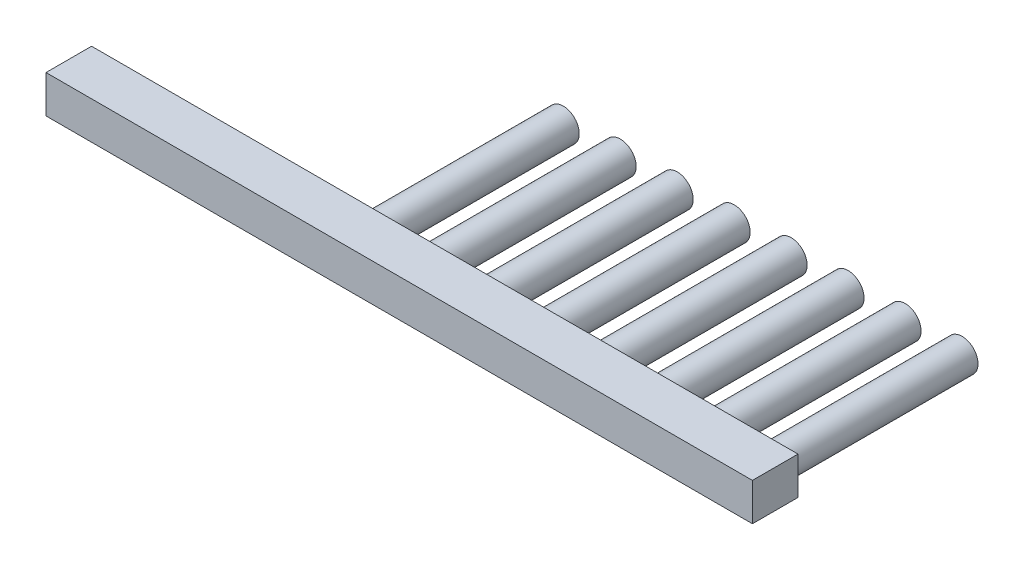
SolidWorks part; units mm, degrees
ref_plane "Front Plane" through (0, 0, 0) normal (0, 0, 1) x (1, 0, 0)
ref_plane "Top Plane" through (0, 0, 0) normal (0, 1, 0) x (1, 0, 0)
ref_plane "Right Plane" through (0, 0, 0) normal (1, 0, 0) x (0, 0, -1)
sketch "Sketch2" plane through (0, 0, 0) normal (0, 0, 1) x (1, 0, 0)
  line L1 (155, 8.25) -> (-155, 8.25)
  line L2 (155, 8.25) -> (155, -8.25)
  line L3 (155, -8.25) -> (-155, -8.25)
  line L4 (-155, 8.25) -> (-155, -8.25)
  line L5 (155, 8.25) -> (-155, -8.25) construction
  line L6 (155, -8.25) -> (-155, 8.25) construction
  point P4 (0, 0)
  point P5 (0, 0)
  dimension "D1" = 16.5
  dimension "D2" = 310
extrude "Boss-Extrude1" add sketch "Sketch2" along normal blind 20
sketch "Sketch3" plane through (0, 0, 0) normal (0, 0, -1) x (-1, 0, 0)
  line L0 (-155, 0) -> (155, 0) construction
  line L1 (-155, -8.25) -> (-155, 8.25) construction
  line L2 (155, 8.25) -> (155, -8.25) construction
  circle A0 centre (-145, 0) radius 7
  point P6 (-145, 0)
  point P9 (-141.0655, 0)
  dimension "D1" = 14
  dimension "D2" = 10
extrude "Boss-Extrude2" add sketch "Sketch3" along normal blind 82
pattern_linear "LPattern1" count 8 spacing 25 along (-1, 0, 0) of "Boss-Extrude2"
sketch "Sketch4" plane through (0, 0, -82) normal (0, 0, -1) x (-1, 0, 0)
  line L0 (-144.5829, 0) -> (-120, 0) construction
